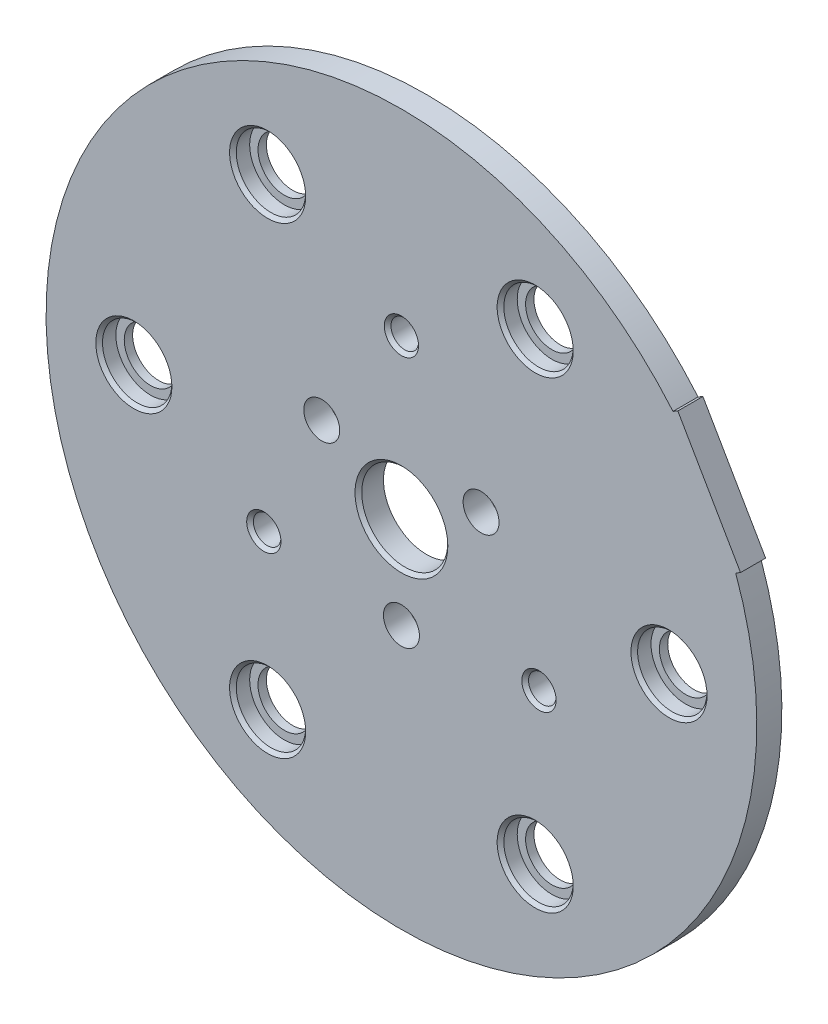
SolidWorks part; units mm, degrees
ref_plane "前视基准面" through (0, 0, 0) normal (0, 0, 1) x (1, 0, 0)
ref_plane "上视基准面" through (0, 0, 0) normal (0, 1, 0) x (1, 0, 0)
ref_plane "右视基准面" through (0, 0, 0) normal (1, 0, 0) x (0, 0, -1)
other "Configuration Table"
sketch "草图1" plane through (0, 0, 0) normal (0, 0, 1) x (1, 0, 0)
  circle A0 centre (0, 0) radius 42.5
  point P0 (0, 0)
  point P19 (0, 0)
  dimension "D1" = 85
extrude "凸台-拉伸1" add sketch "草图1" against normal blind 3 contours A0
sketch "草图2" plane through (0, 0, 0) normal (0, 0, 1) x (1, 0, 0)
  line L0 (0, 0) -> (-32, 0) construction
  circle A1 centre (-32, 0) radius 4.15
  circle A2 centre (-16, 27.7128) radius 4.15
  circle A3 centre (16, 27.7128) radius 4.15
  circle A4 centre (32, 0) radius 4.15
  circle A5 centre (16, -27.7128) radius 4.15
  circle A6 centre (-16, -27.7128) radius 4.15
  point P17 (0, 0)
  dimension "D4" = 8.3
  dimension "D2" = 32
  dimension "D3" = 6
extrude "切除-拉伸1" cut sketch "草图2" against normal through all
sketch "草图3" plane through (0, 0, 0) normal (0, 0, 1) x (1, 0, 0)
  circle A0 centre (0, 0) radius 5.15
  dimension "D1" = 10.3
extrude "切除-拉伸2" cut sketch "草图3" against normal through all
sketch "草图4" plane through (0, 0, -3) normal (0, 0, -1) x (-1, 0, 0)
  circle A0 centre (-16, 27.7128) radius 4.15 construction
  circle A1 centre (-16, 27.7128) radius 4.15
  circle A2 centre (16, 27.7128) radius 4.15 construction
  circle A3 centre (16, 27.7128) radius 4.15
  circle A4 centre (32, 0) radius 4.15 construction
  circle A5 centre (32, 0) radius 4.15
  circle A6 centre (16, -27.7128) radius 4.15 construction
  circle A7 centre (16, -27.7128) radius 4.15
  circle A8 centre (-16, -27.7128) radius 4.15 construction
  circle A9 centre (-16, -27.7128) radius 4.15
  circle A10 centre (-32, 0) radius 4.15 construction
  circle A11 centre (-32, 0) radius 4.15
extrude "拉伸-薄壁1" add sketch "草图4" against normal blind 1 thin thin type one direction reverse wall 1
sketch "草图5" plane through (0, 0, -3) normal (0, 0, -1) x (-1, 0, 0)
  circle A0 centre (-16.4545, -9.5) radius 1.65 construction
  circle A1 centre (-16.4545, -9.5) radius 1.65
  circle A2 centre (0, 19) radius 1.65 construction
  circle A3 centre (0, 19) radius 1.65
  circle A4 centre (16.4545, -9.5) radius 1.65 construction
  circle A5 centre (16.4545, -9.5) radius 1.65
extrude "切除-拉伸3" cut sketch "草图5" against normal up to next
sketch "草图6" plane through (0, 0, 0) normal (0, 0, 1) x (1, 0, 0)
  circle A0 centre (0, 19) radius 1.65 construction
  circle A1 centre (0, 19) radius 1.65
  circle A2 centre (-16.4545, -9.5) radius 1.65 construction
  circle A3 centre (-16.4545, -9.5) radius 1.65
  circle A4 centre (16.4545, -9.5) radius 1.65 construction
  circle A5 centre (16.4545, -9.5) radius 1.65
extrude "拉伸-薄壁2" [suppressed] add sketch "草图6" along normal blind 10 thin
chamfer "倒角1" [suppressed] distance 3 angle 75
sketch "草图7" plane through (0, 0, 0) normal (0, 0, 1) x (1, 0, 0)
  circle A1 centre (9.5263, 5.5) radius 2.15
  circle A2 centre (0, -11) radius 2.15
  circle A3 centre (-9.5263, 5.5) radius 2.15
  point P9 (0, 0)
  dimension "D1" = 4.3
  dimension "D2" = 3
extrude "切除-拉伸4" cut sketch "草图7" against normal up to next
chamfer "倒角2" distance 0.4 angle 45 10 edges at (5.15, 0, 0) (18.1045, -9.5, 0) (1.65, 19, 0) (-14.8045, -9.5, 0) (20.15, -27.7128, 0) (-11.85, -27.7128, 0) (-27.85, 0, 0) (36.15, 0, 0) (20.15, 27.7128, 0) (-11.85, 27.7128, 0)
sketch "草图8" plane through (0, 0, 0) normal (0, 0, 1) x (1, 0, 0)
  line L0 (33.0561, 27.7452) -> (40.5561, 14.7548) construction
  line L1 (33.0561, 27.7452) -> (40.5561, 14.7548)
extrude "拉伸-薄壁3" add sketch "草图8" against normal up to surface (3 mm away) thin
